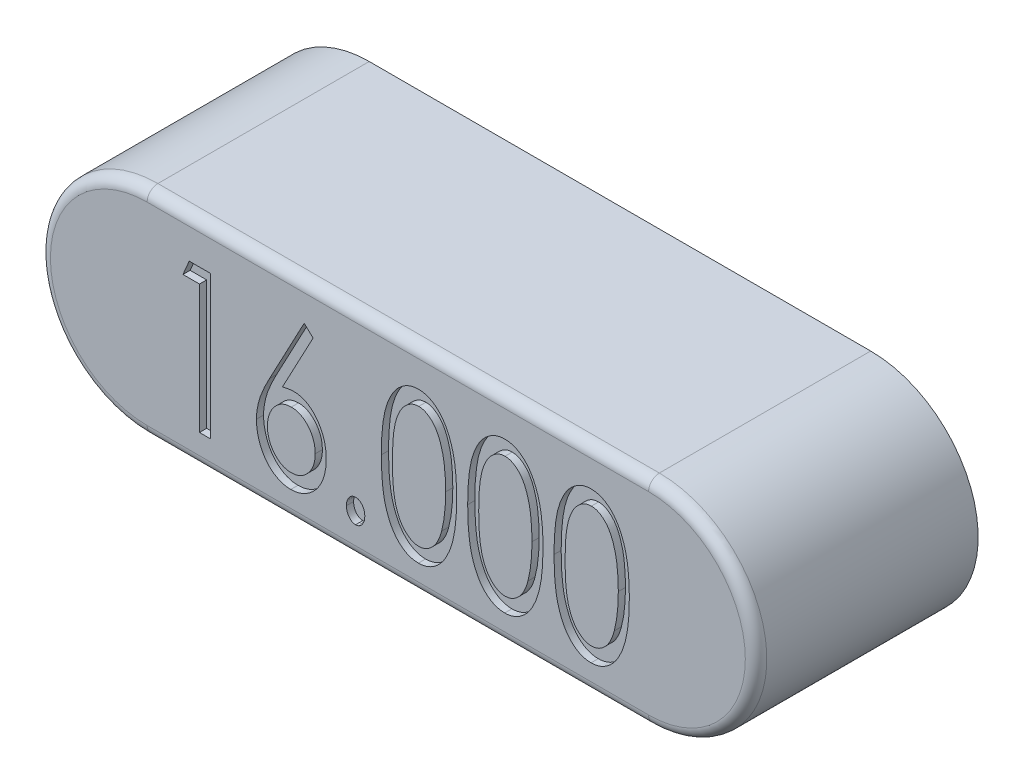
SolidWorks part; units mm, degrees
material "1.4000 (X6Cr13)"
ref_plane "Plan de face" through (0, 0, 0) normal (0, 0, 1) x (1, 0, 0)
ref_plane "Plan de dessus" through (0, 0, 0) normal (0, 1, 0) x (1, 0, 0)
ref_plane "Plan de droite" through (0, 0, 0) normal (1, 0, 0) x (0, 0, -1)
sketch "Esquisse1" plane through (0, 0, 0) normal (0, 0, 1) x (1, 0, 0)
  line L0 (-3.5, 0) -> (3.5, 0) construction
  line L1 (-3.5, 1.5) -> (3.5, 1.5)
  line L2 (-3.5, -1.5) -> (3.5, -1.5)
  arc A0 (-3.5, 1.5) -> (-3.5, -1.5) centre (-3.5, 0) ccw
  arc A1 (3.5, -1.5) -> (3.5, 1.5) centre (3.5, 0) ccw
  point P2 (0, 0)
  point P8 (-5, 0)
  point P9 (5, 0)
  dimension "D1" = 10
  dimension "D2" = 3
extrude "Boss.-Extru.1" add sketch "Esquisse1" along normal blind 3.1
fillet "Congé1" radius 0.15 4 edges at (5, 0, 3.1) (0, -1.5, 3.1) (-5, 0, 3.1) (0, 1.5, 3.1)
sketch "Esquisse2" plane through (0, 0, 3.1) normal (0, 0, 1) x (1, 0, 0)
  line L0 (-3.5, -1.0695) -> (3.5, -1.0695) construction
  text T0 "16.000" font "Century Gothic" height 2
extrude "Enlèv. mat.-Extru.1" cut sketch "Esquisse2" against normal blind 0.1
